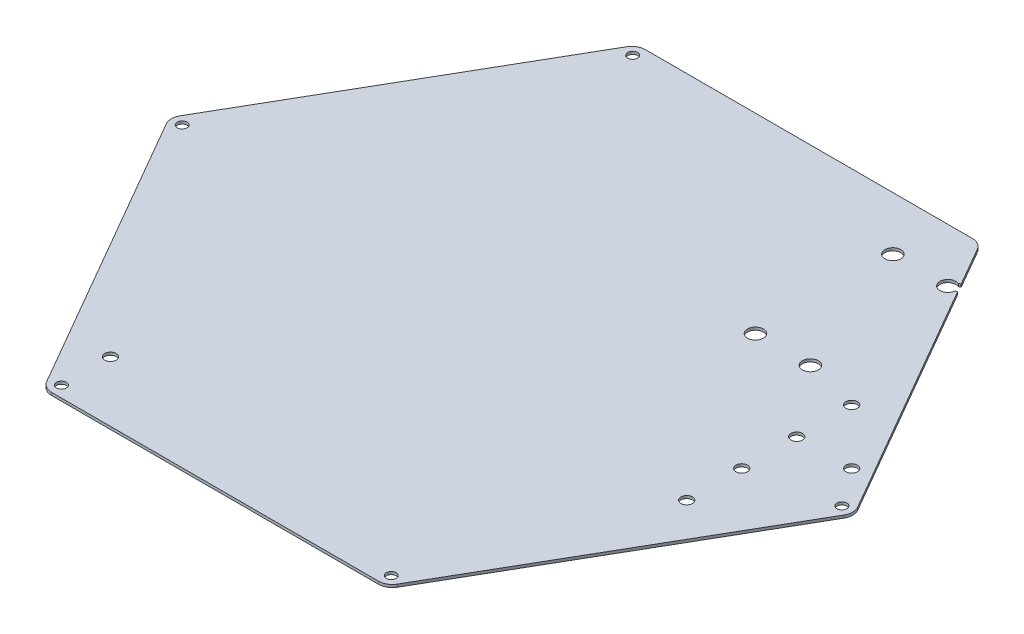
SolidWorks part; units mm, degrees
material "Thornel Mat VMA"
ref_plane "Front Plane" through (0, 0, 0) normal (0, 0, 1) x (1, 0, 0)
ref_plane "Top Plane" through (0, 0, 0) normal (0, 1, 0) x (1, 0, 0)
ref_plane "Right Plane" through (0, 0, 0) normal (1, 0, 0) x (0, 0, -1)
sketch "Sketch1" plane through (0, 0, 0) normal (0, 1, 0) x (1, 0, 0)
  line L1 (62.3538, 0) -> (187.0615, 0)
  line L2 (187.0615, 0) -> (249.4153, 108)
  line L3 (249.4153, 108) -> (187.0615, 216)
  line L4 (187.0615, 216) -> (62.3538, 216)
  line L5 (62.3538, 216) -> (0, 108)
  line L6 (0, 108) -> (62.3538, 0)
  circle A0 centre (124.7077, 108) radius 108 construction
  dimension "D1" = 216
extrude "Boss-Extrude1" add sketch "Sketch1" along normal blind 1
fillet "Fillet1" radius 5 6 edges at (0, 0.5, -108) (62.3538, 0.5, -216) (187.0615, 0.5, -216) (249.4153, 0.5, -108) (62.3538, 0.5, 0) (187.0615, 0.5, 0)
sketch "Sketch2" plane through (0, 1, 0) normal (0, 1, 0) x (1, 0, 0)
  line L0 (124.7077, 0) -> (124.7077, 216) construction
  line L1 (65.2406, 0) -> (184.1747, 0) construction
  line L2 (184.1747, 216) -> (65.2406, 216) construction
  line L3 (124.7077, 108) -> (244.7077, 108) construction
  line L4 (174.7077, 196.57) -> (194.7077, 196.57)
  line L5 (174.7077, 196.57) -> (174.7077, 146.57)
  line L6 (174.7077, 146.57) -> (194.7077, 146.57)
  line L7 (194.7077, 196.57) -> (194.7077, 146.57)
  line L8 (174.7077, 196.57) -> (194.7077, 146.57) construction
  line L9 (174.7077, 146.57) -> (194.7077, 196.57) construction
  line L10 (124.7077, 108) -> (64.7077, 211.923) construction
  line L11 (124.7077, 108) -> (4.7077, 108) construction
  line L12 (124.7077, 108) -> (64.7077, 4.077) construction
  line L13 (124.7077, 108) -> (184.7077, 4.077) construction
  point P6 (184.7077, 171.57)
  dimension "D1" = 50
  dimension "D2" = 20
  dimension "D3" = 50
  dimension "D4" = 38.57
  dimension "D5" = 120
  dimension "D6" = 60
  dimension "D7" = 60
hole_wizard "M5 Clearance Hole1" positions "Sketch4" profile "Sketch5" hole size "M5" standard "ANSI Metric"
sketch "Sketch4" plane through (0, 1, 0) normal (0, 1, 0) x (1, 0, 0)
  point P0 (174.7077, 146.57)
  point P3 (194.7077, 146.57)
  point P6 (194.7077, 196.57)
  point P9 (174.7077, 196.57)
sketch "Sketch5" plane through (174.7077, 1, -146.57) normal (1, 0, 0) x (0, 0, 1)
  line L0 (0, 0) -> (0, 6.7425)
  line L1 (0, 6.7425) -> (2.9, 5)
  line L2 (2.9, 5) -> (2.9, 0)
  line L5 (2.9, 0) -> (0, 0)
  line L10 (0, 6.7425) -> (-2.9, 5) construction
  line L11 (0, -6.35) -> (0, 107.95) construction
  dimension "Hole Dia." = 5.8
  dimension "Hole Depth" = 5
  dimension "Drill Angle" = 118
hole_wizard "M3 Clearance Hole1" positions "Sketch7" profile "Sketch8" hole size "M3" standard "ANSI Metric" end condition through all
sketch "Sketch7" plane through (0, 1, 0) normal (0, 1, 0) x (1, 0, 0)
  point P0 (4.7077, 108)
  point P3 (64.7077, 211.923)
  point P6 (244.7077, 108)
  point P9 (184.7077, 4.077)
  point P12 (64.7077, 4.077)
sketch "Sketch8" plane through (4.7077, 1, -108) normal (1, 0, 0) x (0, 0, 1)
  line L0 (0, 0) -> (0, 1)
  line L1 (0, 1) -> (1.8, 1)
  line L2 (1.8, 1) -> (1.8, 0)
  line L5 (1.8, 0) -> (0, 0)
  line L11 (0, -6.35) -> (0, 107.95) construction
  dimension "Thru Hole Dia." = 3.6
  dimension "Thru Hole Depth" = 1
sketch "Sketch9" plane through (0, 1, 0) normal (0, 1, 0) x (1, 0, 0)
  line L0 (195.8353, 199.2418) -> (196.5115, 199.6322)
  line L1 (247.9719, 110.5) -> (188.5049, 213.5) construction
  line L2 (197.5853, 196.2107) -> (198.2615, 196.6011)
  line L3 (196.5115, 199.6322) -> (198.2615, 196.6011)
  line L4 (195.8353, 199.2418) -> (197.5853, 196.2107)
  circle A0 centre (194.7077, 196.57) radius 2.9 construction
  dimension "D1" = 3.5
extrude "Cut-Extrude1" cut sketch "Sketch9" against normal through all
sketch "Sketch10" plane through (0, 1, 0) normal (0, 1, 0) x (1, 0, 0)
  line L0 (58.9342, 211.923) -> (64.7077, 211.923) construction
  line L1 (64.7077, 211.923) -> (64.7077, 21.923) construction
  line L2 (64.7077, 21.923) -> (48.6307, 21.923) construction
  line L3 (58.9342, 211.923) -> (4.7077, 118) construction
  line L4 (48.6307, 21.923) -> (4.7077, 98) construction
  line L5 (4.7077, 98) -> (4.7077, 118) construction
  line L6 (194.7077, 196.57) -> (194.7077, 146.57) construction
  line L7 (60.9105, 213.5) -> (1.4434, 110.5) construction
  line L8 (1.4434, 105.5) -> (60.9105, 2.5) construction
  line L9 (194.7077, 171.57) -> (214.7077, 171.57) construction
  line L10 (214.7077, 171.57) -> (214.7077, 141.57) construction
  line L11 (214.7077, 101.57) -> (214.7077, 141.57) construction
  line L12 (214.7077, 101.57) -> (214.7077, 61.57) construction
  line L13 (214.7077, 121.57) -> (234.7077, 121.57) construction
  circle A0 centre (4.7077, 108) radius 2.1 construction
  circle A1 centre (4.7077, 108) radius 1.8 construction
  circle A2 centre (64.7077, 211.923) radius 1.8 construction
  circle A3 centre (64.7077, 21.923) radius 2.1
  circle A4 centre (64.7077, 211.923) radius 2.1 construction
  circle A5 centre (214.7077, 141.57) radius 2.1
  circle A6 centre (214.7077, 121.57) radius 2.1
  circle A7 centre (214.7077, 101.57) radius 2.1
  circle A8 centre (214.7077, 81.57) radius 2.1
  circle A9 centre (214.7077, 61.57) radius 2.1 construction
  circle A10 centre (234.7077, 121.57) radius 2.1
  point P28 (214.7077, 121.57)
  dimension "D1" = 20
  dimension "D2" = 190
  dimension "D3" = 4.2
  dimension "D4" = 20
  dimension "D5" = 30
  dimension "D6" = 20
extrude "Cut-Extrude2" cut sketch "Sketch10" against normal through all
